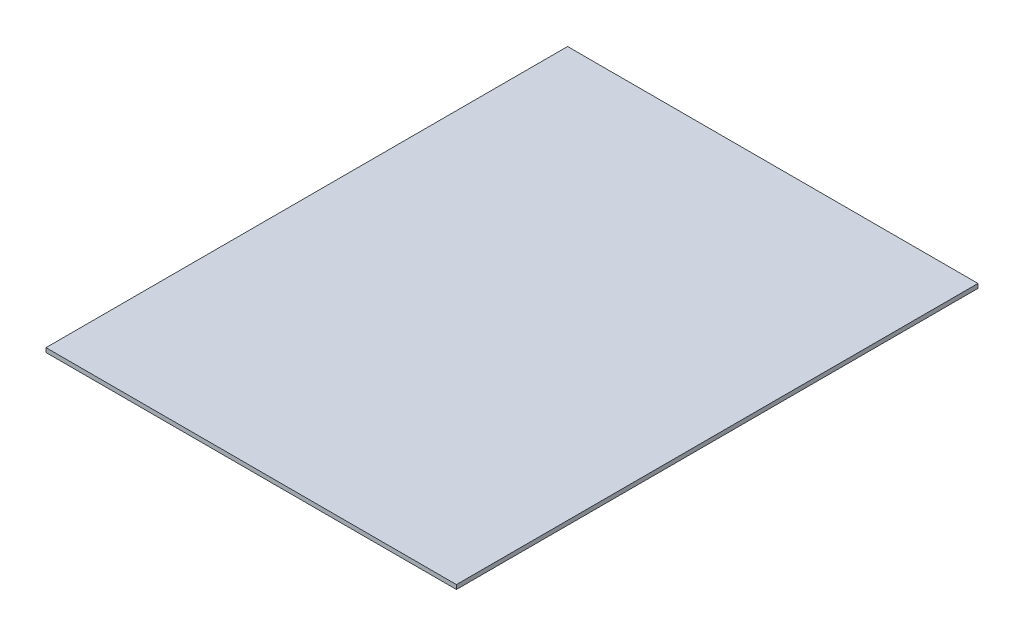
SolidWorks part; units mm, degrees
ref_plane "Front Plane" through (0, 0, 0) normal (0, 0, 1) x (1, 0, 0)
ref_plane "Top Plane" through (0, 0, 0) normal (0, 1, 0) x (1, 0, 0)
ref_plane "Right Plane" through (0, 0, 0) normal (1, 0, 0) x (0, 0, -1)
sketch "Sketch1" plane through (0, 0, 0) normal (0, 1, 0) x (1, 0, 0)
  line L1 (-152.4, -193.675) -> (152.4, -193.675)
  line L2 (-152.4, -193.675) -> (-152.4, 193.675)
  line L3 (-152.4, 193.675) -> (152.4, 193.675)
  line L4 (152.4, -193.675) -> (152.4, 193.675)
  line L5 (0, 193.675) -> (0, -193.675) construction
  line L6 (-152.4, 0) -> (152.4, 0) construction
  point P0 (0, 0)
  dimension "D1" = 304.8
  dimension "D2" = 387.35
extrude "Boss-Extrude1" add sketch "Sketch1" along normal blind 3.175
